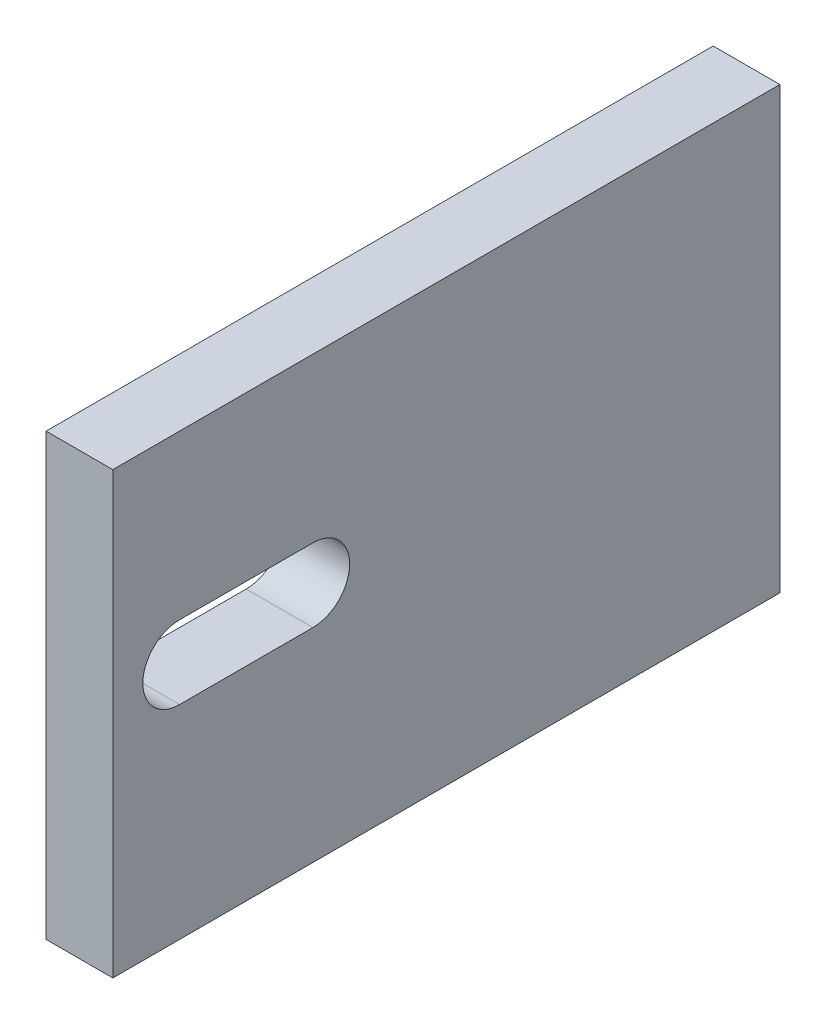
SolidWorks part; units mm, degrees
ref_plane "Front Plane" through (0, 0, 0) normal (0, 0, 1) x (1, 0, 0)
ref_plane "Top Plane" through (0, 0, 0) normal (0, 1, 0) x (1, 0, 0)
ref_plane "Right Plane" through (0, 0, 0) normal (1, 0, 0) x (0, 0, -1)
sketch "Sketch1" plane through (0, 0, 0) normal (1, 0, 0) x (0, 0, -1)
  line L0 (-20, 1.5) -> (-10, 1.5) construction
  line L1 (-25, -16.5) -> (25, -16.5)
  line L2 (-25, -16.5) -> (-25, 16.5)
  line L3 (-25, 16.5) -> (25, 16.5)
  line L4 (25, -16.5) -> (25, 16.5)
  line L5 (-25, -16.5) -> (25, 16.5) construction
  line L6 (-25, 16.5) -> (25, -16.5) construction
  line L7 (-20, 4.25) -> (-10, 4.25)
  line L8 (-20, -1.25) -> (-10, -1.25)
  arc A0 (-20, 4.25) -> (-20, -1.25) centre (-20, 1.5) ccw
  arc A1 (-10, -1.25) -> (-10, 4.25) centre (-10, 1.5) ccw
  point P0 (0, 0)
  point P8 (-15, 1.5)
  dimension "D5" = 10
  dimension "D1" = 33
  dimension "D2" = 50
  dimension "D3" = 15
  dimension "D4" = 10
extrude "Extrude1" add sketch "Sketch1" along normal blind 5
